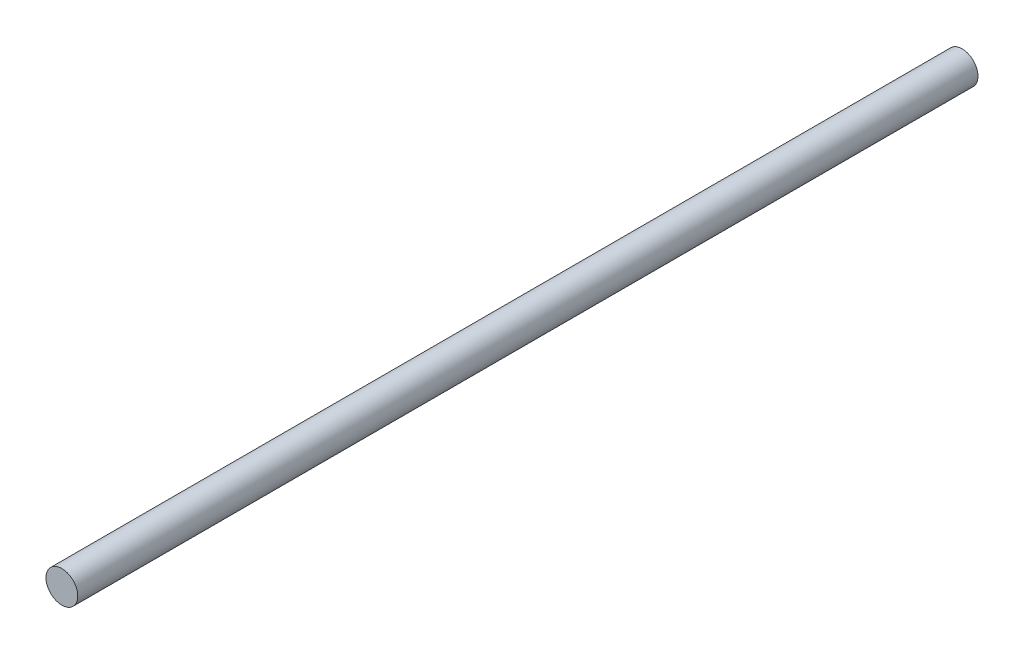
SolidWorks part; units mm, degrees
ref_plane "Plan de face" through (0, 0, 0) normal (0, 0, 1) x (1, 0, 0)
ref_plane "Plan de dessus" through (0, 0, 0) normal (0, 1, 0) x (1, 0, 0)
ref_plane "Plan de droite" through (0, 0, 0) normal (1, 0, 0) x (0, 0, -1)
sketch "Esquisse1" plane through (0, 0, 0) normal (0, 0, 1) x (1, 0, 0)
  circle A0 centre (0, 0) radius 3
  dimension "D1" = 6
extrude "Boss.-Extru.1" add sketch "Esquisse1" along normal blind 170
